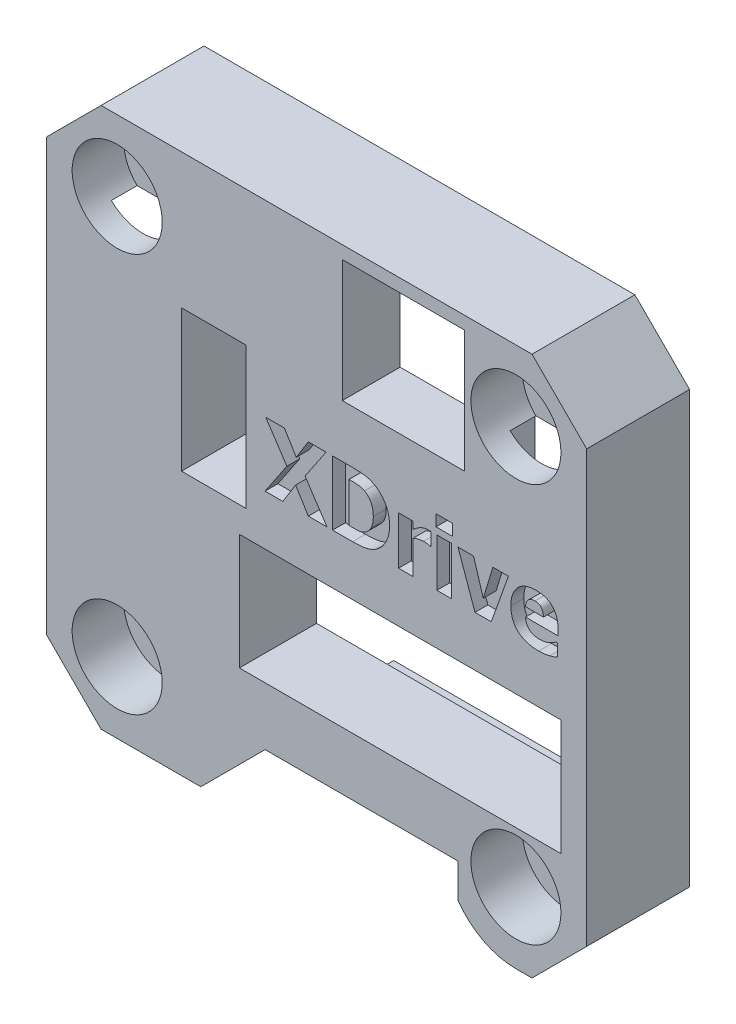
SolidWorks part; units mm, degrees
ref_plane "前视基准面" through (0, 0, 0) normal (0, 0, 1) x (1, 0, 0)
ref_plane "上视基准面" through (0, 0, 0) normal (0, 1, 0) x (1, 0, 0)
ref_plane "右视基准面" through (0, 0, 0) normal (1, 0, 0) x (0, 0, -1)
sketch "草图1" plane through (0, 0, 0) normal (0, 0, 1) x (1, 0, 0)
  line L0 (21, 16.75) -> (21, -16.75)
  line L1 (-16.75, 21) -> (16.75, 21)
  line L2 (-16.75, -21) -> (16.75, -21)
  line L3 (-21, 16.75) -> (-21, -16.75)
  line L4 (16.75, 21) -> (21, 16.75)
  line L5 (21, -16.75) -> (16.75, -21)
  line L6 (-16.75, -21) -> (-21, -16.75)
  line L7 (-21, 16.75) -> (-16.75, 21)
extrude "凸台-拉伸1" add sketch "草图1" along normal blind 8
sketch "草图5" plane through (0, 0, 8) normal (0, 0, 1) x (1, 0, 0)
  circle A0 centre (-15.5, 15.5) radius 3.5
  circle A1 centre (15.5, 15.5) radius 3.5
  circle A2 centre (15.5, -15.5) radius 3.5
  circle A3 centre (-15.5, -15.5) radius 3.5
extrude "切除-拉伸3" cut sketch "草图5" against normal blind 4
sketch "草图6" plane through (0, 0, 4) normal (0, 0, 1) x (1, 0, 0)
  circle A0 centre (-15.5, 15.5) radius 1.6
  circle A1 centre (15.5, 15.5) radius 1.6
  circle A2 centre (15.5, -15.5) radius 1.6
  circle A3 centre (-15.5, -15.5) radius 1.6
extrude "切除-拉伸4" cut sketch "草图6" against normal through all
sketch "草图2" plane through (0, 0, 0) normal (0, 0, -1) x (-1, 0, 0)
  line L0 (21, 16.75) -> (21, -16.75) construction
  line L1 (21, 13) -> (11.5, 13)
  line L2 (21, 13) -> (21, -13)
  line L3 (21, -13) -> (11.5, -13)
  line L4 (11.5, 13) -> (11.5, -13)
extrude "切除-拉伸1" cut sketch "草图2" against normal blind 6
sketch "草图4" plane through (0, 0, 0) normal (0, 0, -1) x (-1, 0, 0)
  line L1 (10.5, 10.5) -> (5.5, 10.5)
  line L2 (10.5, 10.5) -> (10.5, -0.5)
  line L3 (10.5, -0.5) -> (5.5, -0.5)
  line L4 (5.5, 10.5) -> (5.5, -0.5)
extrude "切除-拉伸2" cut sketch "草图4" against normal through all
sketch "草图7" plane through (0, 0, 0) normal (0, 0, -1) x (-1, 0, 0)
  line L1 (-2, 20) -> (-11.5, 20)
  line L2 (-2, 20) -> (-2, 10.5)
  line L3 (-2, 10.5) -> (-11.5, 10.5)
  line L4 (-11.5, 20) -> (-11.5, 10.5)
extrude "切除-拉伸5" cut sketch "草图7" against normal through all
sketch "草图8" plane through (0, 0, 0) normal (0, 0, -1) x (-1, 0, 0)
  line L7 (-11, -18.6623) -> (-11, -16)
  line L8 (16.75, -21) -> (-16.75, -21) construction
  line L9 (-11, -16) -> (4, -16)
  line L10 (4, -16) -> (9, -21)
  line L11 (9, -21) -> (-15.5, -21)
  arc A0 (-15.5, -21) -> (-11, -18.6623) centre (-15.5, -15.5) ccw
extrude "切除-拉伸6" cut sketch "草图8" against normal through all
sketch "草图9" plane through (0, 0, 0) normal (0, 0, -1) x (-1, 0, 0)
  line L0 (16.75, -21) -> (9, -21) construction
  line L1 (2, -21) -> (12.5, -21)
  line L2 (2, -21) -> (2, -12.5)
  line L3 (2, -12.5) -> (12.5, -12.5)
  line L4 (12.5, -21) -> (12.5, -12.5)
extrude "切除-拉伸7" cut sketch "草图9" against normal blind 3.5
sketch "草图10" plane through (0, 0, 0) normal (0, 0, -1) x (-1, 0, 0)
  line L2 (-20, 13) -> (-20, -0.5)
  line L3 (-20, -0.5) -> (4.5, -0.5)
  line L4 (4.5, 11.5) -> (4.5, -0.5)
  line L6 (-12.5, 13) -> (-20, 13)
  line L9 (-1, 20) -> (10.5, 20)
  line L10 (10.5, 20) -> (10.5, 11.5)
  line L11 (10.5, 11.5) -> (4.5, 11.5)
  line L12 (-12.5, 13) -> (-12.5, 9.5)
  line L13 (-12.5, 9.5) -> (-1, 9.5)
  line L14 (-1, 9.5) -> (-1, 20)
extrude "切除-拉伸8" cut sketch "草图10" against normal blind 6
sketch "草图11" plane through (0, 0, 0) normal (0, 0, -1) x (-1, 0, 0)
  line L1 (-20, -0.5) -> (11.5, -0.5)
  line L2 (-20, -0.5) -> (-20, -13)
  line L3 (-20, -13) -> (11.5, -13)
  line L4 (11.5, -0.5) -> (11.5, -13)
extrude "切除-拉伸9" cut sketch "草图11" against normal blind 2
sketch "草图13" plane through (0, 0, 2) normal (0, 0, -1) x (-1, 0, 0)
  line L1 (-19, -2.5) -> (6, -2.5)
  line L2 (-19, -2.5) -> (-19, -11.5)
  line L3 (-19, -11.5) -> (6, -11.5)
  line L4 (6, -2.5) -> (6, -11.5)
sketch "草图14" plane through (0, 0, 8) normal (0, 0, 1) x (1, 0, 0)
  text T0 "<b>XDrive</b>" font "Tahoma" height 5
extrude "切除-拉伸12" cut sketch "草图14" against normal blind 1
extrude "切除-拉伸13" cut sketch "草图13" against normal through all
sketch "草图15" plane through (0, 0, 0) normal (0, 0, -1) x (-1, 0, 0)
  line L0 (-12.5, 13) -> (-11.5, 13)
  line L1 (-11.5, 20) -> (-11.5, 10.5) construction
  line L2 (-11.5, 13) -> (-11.5, 10.5)
  line L3 (-11.5, 10.5) -> (-2, 10.5)
  line L4 (-2, 10.5) -> (-2, 20)
  line L5 (-2, 20) -> (-1, 20)
  line L6 (-1, 20) -> (-1, 9.5)
  line L7 (-1, 9.5) -> (-12.5, 9.5)
  line L8 (-12.5, 9.5) -> (-12.5, 13)
extrude "切除-拉伸14" cut sketch "草图15" against normal blind 3.5
sketch "草图16" plane through (0, 0, 0) normal (0, 0, -1) x (-1, 0, 0)
  line L0 (4.5, -0.5) -> (5.5, -0.5)
  line L1 (5.5, -0.5) -> (5.5, 10.5)
  line L2 (5.5, 10.5) -> (10.5, 10.5)
  line L3 (10.5, 10.5) -> (10.5, -0.5)
  line L4 (10.5, -0.5) -> (11.5, -0.5)
  line L7 (4.5, 11.5) -> (4.5, -0.5)
  line L8 (10.5, 11.5) -> (10.5, 13)
  line L9 (10.5, 11.5) -> (10.5, 20) construction
  line L10 (10.5, 13) -> (11.5, 13)
  line L12 (4.5, 11.5) -> (10.5, 11.5)
  line L13 (11.5, 13) -> (11.5, -0.5)
extrude "切除-拉伸16" cut sketch "草图16" against normal blind 2
